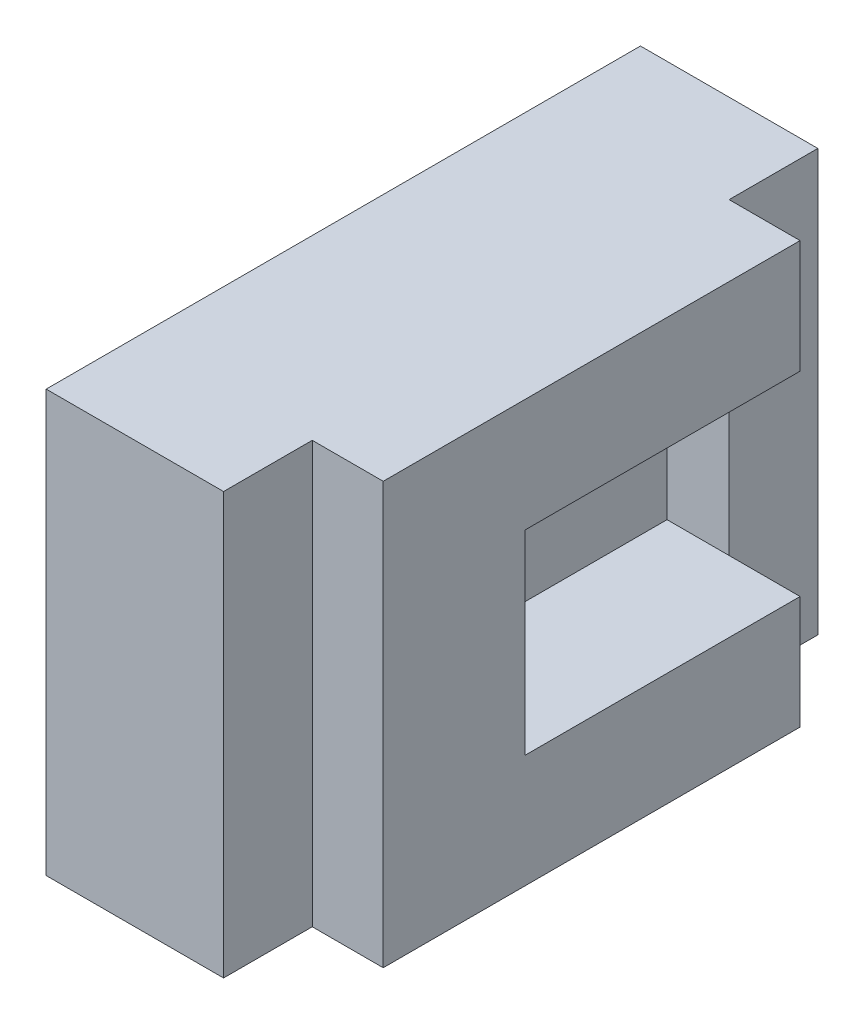
SolidWorks part; units mm, degrees
ref_plane "Front Plane" through (0, 0, 0) normal (0, 0, 1) x (1, 0, 0)
ref_plane "Top Plane" through (0, 0, 0) normal (0, 1, 0) x (1, 0, 0)
ref_plane "Right Plane" through (0, 0, 0) normal (1, 0, 0) x (0, 0, -1)
sketch "Sketch1" plane through (0, 0, 0) normal (1, 0, 0) x (0, 0, -1)
  line L1 (0, 0) -> (67, 0)
  line L2 (0, 0) -> (0, -47.5)
  line L3 (0, -47.5) -> (67, -47.5)
  line L4 (67, 0) -> (67, -47.5)
  dimension "D1" = 67
  dimension "D2" = 47.5
extrude "Boss-Extrude1" add sketch "Sketch1" along normal blind 28
sketch "Sketch2" plane through (28, 0, 0) normal (1, 0, 0) x (0, 0, -1)
  line L0 (67, -47.5) -> (67, 0) construction
  line L1 (26, -12.75) -> (57, -12.75)
  line L2 (26, -12.75) -> (26, -34.75)
  line L3 (26, -34.75) -> (57, -34.75)
  line L4 (57, -12.75) -> (57, -34.75)
  point P4 (57, -23.75)
  point P7 (67, -23.75)
  dimension "D1" = 31
  dimension "D2" = 22
  dimension "D3" = 10
extrude "Cut-Extrude1" cut sketch "Sketch2" against normal blind 15
sketch "Sketch3" plane through (28, 0, 0) normal (1, 0, 0) x (0, 0, -1)
  line L0 (67, 0) -> (0, 0) construction
  line L1 (0, -47.5) -> (10, -47.5)
  line L2 (0, -47.5) -> (0, 0)
  line L3 (0, 0) -> (10, 0)
  line L4 (10, -47.5) -> (10, 0)
  line L5 (0, -47.5) -> (67, -47.5) construction
  line L6 (67, 0) -> (57, 0)
  line L7 (67, 0) -> (67, -47.5)
  line L8 (67, -47.5) -> (57, -47.5)
  line L9 (57, 0) -> (57, -47.5)
  dimension "D1" = 10
extrude "Cut-Extrude2" cut sketch "Sketch3" against normal blind 8
